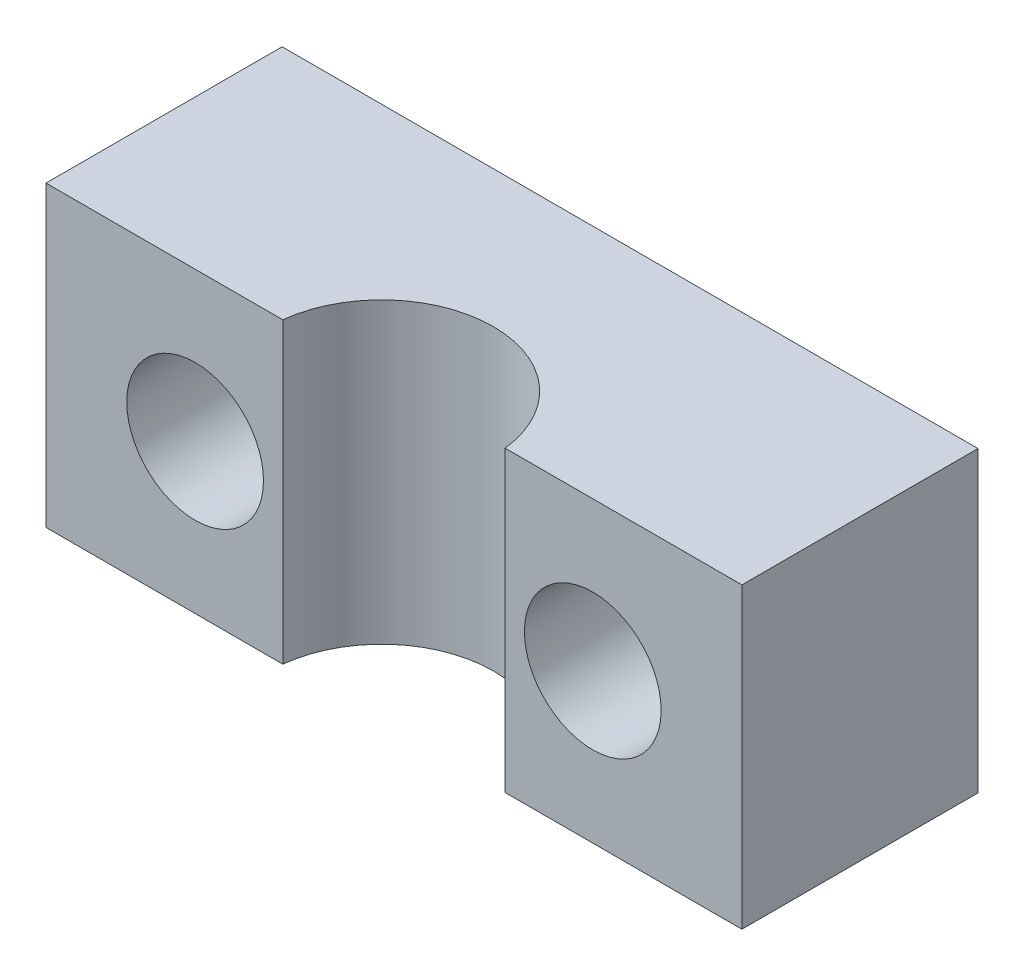
SolidWorks part; units mm, degrees
ref_plane "前视基准面" through (0, 0, 0) normal (0, 0, 1) x (1, 0, 0)
ref_plane "上视基准面" through (0, 0, 0) normal (0, 1, 0) x (1, 0, 0)
ref_plane "右视基准面" through (0, 0, 0) normal (1, 0, 0) x (0, 0, -1)
sketch "草图1" plane through (0, 0, 0) normal (0, 0, 1) x (1, 0, 0)
  line L78 (1281.1068, 1010.159) -> (1268.3302, 1010.159) construction
  line L80 (1258.1612, 1002.61) -> (1258.1612, 1016.8822) construction
  line L81 (1265.1068, 1010.159) -> (1252.3302, 1010.159) construction
  line L82 (1252.1612, 1004.159) -> (1252.1612, 1016.159)
  line L83 (1280.1612, 1004.159) -> (1280.1612, 1016.159)
  line L84 (1252.1612, 1004.159) -> (1280.1612, 1004.159)
  line L85 (1252.1612, 1016.159) -> (1280.1612, 1016.159)
  line L88 (1266.1612, 1002.0824) -> (1266.1612, 1018.5251) construction
  circle A5 centre (1274.1612, 1010.159) radius 2.75
  circle A8 centre (1258.1612, 1010.159) radius 2.75
extrude "拉伸1" add sketch "草图1" along normal blind 9.5
sketch "草图2" plane through (0, 0, 0) normal (0, 0, -1) x (-1, 0, 0)
  circle A0 centre (-1258.1612, 1010.159) radius 4.75
  circle A1 centre (-1274.1612, 1010.159) radius 4.75
  dimension "D1" = 9.5
  dimension "D2" = 9.5
extrude "拉伸2" cut sketch "草图2" against normal blind 5
sketch "草图3" plane through (0, 1016.159, 0) normal (0, 1, 0) x (1, 0, 0)
  line L2 (1280.1612, -9.5) -> (1252.1612, -9.5) construction
  circle A0 centre (1266.1612, -10) radius 4.5
  dimension "D1" = 9
  dimension "D2" = 0.5
extrude "拉伸3" cut sketch "草图3" against normal through all
